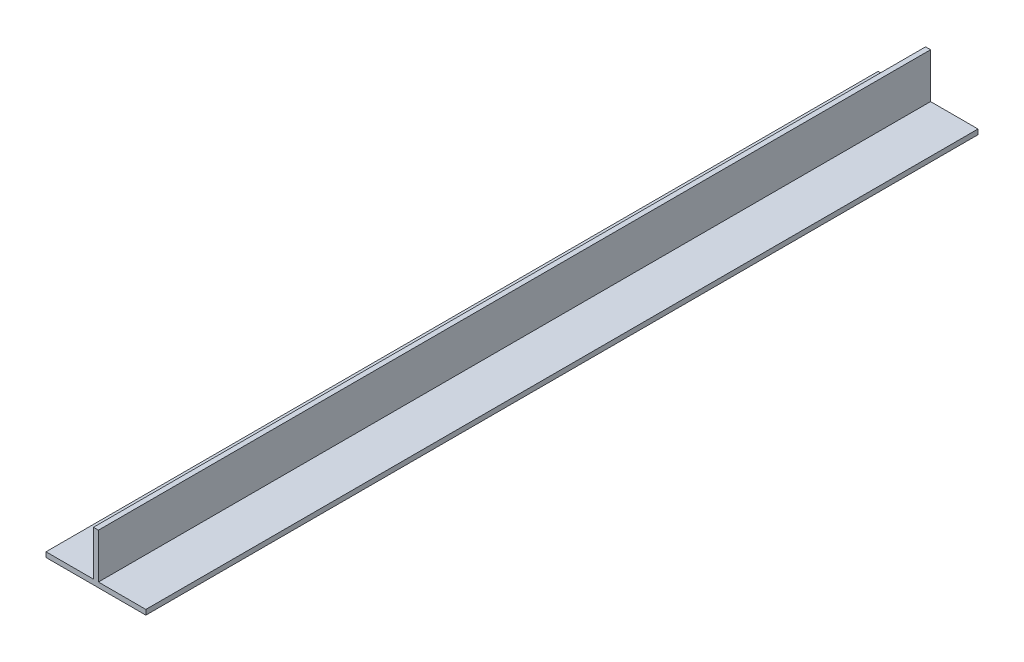
SolidWorks part; units mm, degrees
ref_plane "Front Plane" through (0, 0, 0) normal (0, 0, 1) x (1, 0, 0)
ref_plane "Top Plane" through (0, 0, 0) normal (0, 1, 0) x (1, 0, 0)
ref_plane "Right Plane" through (0, 0, 0) normal (1, 0, 0) x (0, 0, -1)
sketch "Sketch1" plane through (0, 0, 0) normal (0, 0, 1) x (1, 0, 0)
  line L0 (0, 0) -> (60, 0)
  line L1 (60, 0) -> (60, 3)
  line L2 (60, 3) -> (31.5, 3)
  line L3 (31.5, 3) -> (31.5, 30)
  line L4 (31.5, 30) -> (28.5, 30)
  line L5 (28.5, 30) -> (28.5, 3)
  line L6 (28.5, 3) -> (0, 3)
  line L7 (0, 3) -> (0, 0)
  dimension "D1" = 3
  dimension "D2" = 3
  dimension "D3" = 3
  dimension "D4" = 60
  dimension "D5" = 28.5
  dimension "D6" = 30
extrude "Boss-Extrude1" add sketch "Sketch1" along normal blind 500
